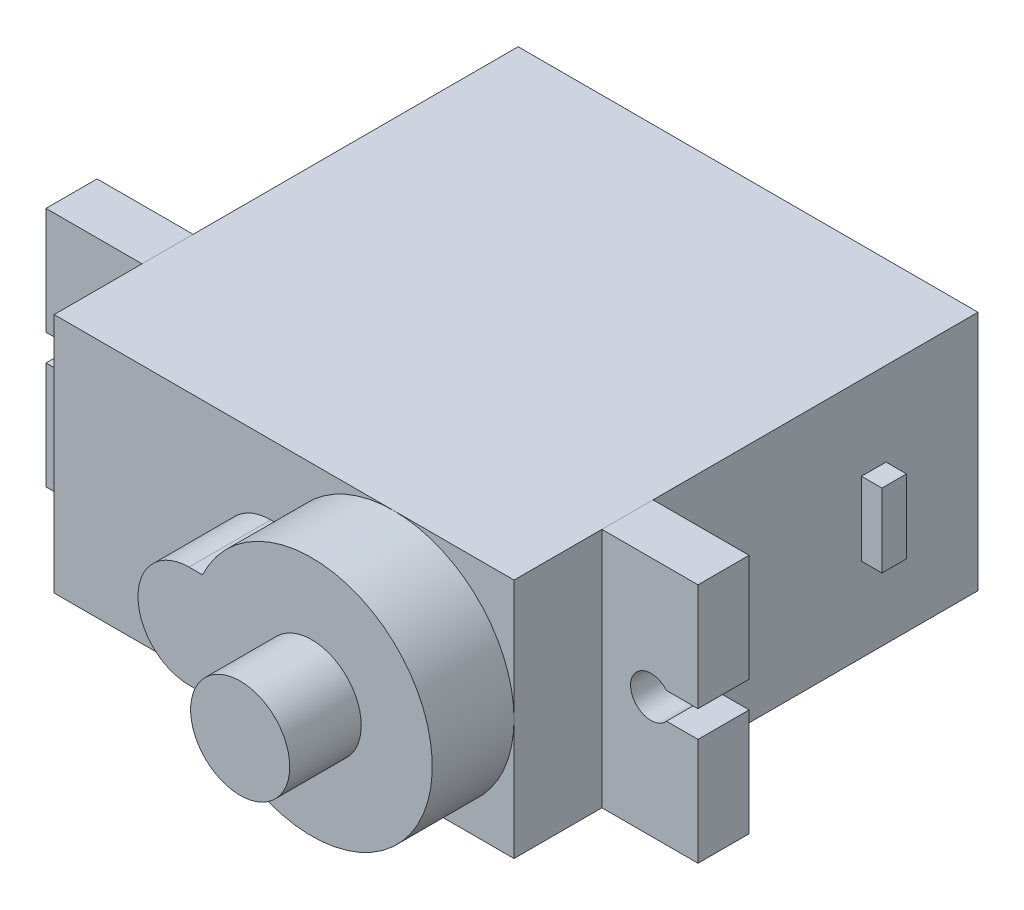
SolidWorks part; units mm, degrees
ref_plane "Alzado" through (0, 0, 0) normal (0, 0, 1) x (1, 0, 0)
ref_plane "Planta" through (0, 0, 0) normal (0, 1, 0) x (1, 0, 0)
ref_plane "Vista lateral" through (0, 0, 0) normal (1, 0, 0) x (0, 0, -1)
sketch "Croquis1" plane through (0, 0, 0) normal (0, 0, 1) x (1, 0, 0)
  line L1 (-11.25, -5.9) -> (11.25, -5.9)
  line L2 (-11.25, -5.9) -> (-11.25, 5.9)
  line L3 (-11.25, 5.9) -> (11.25, 5.9)
  line L4 (11.25, -5.9) -> (11.25, 5.9)
  line L5 (-11.25, -5.9) -> (11.25, 5.9) construction
  line L6 (-11.25, 5.9) -> (11.25, -5.9) construction
  point P0 (0, 0)
  dimension "D1" = 22.5
  dimension "D2" = 11.8
extrude "Saliente-Extruir2" add sketch "Croquis1" along normal blind 15.9
sketch "Croquis2" plane through (0, 0, 15.9) normal (0, 0, 1) x (1, 0, 0)
  line L0 (-11.25, -5.9) -> (11.25, -5.9) construction
  line L5 (0, 0) -> (0, 5.9) construction
  line L6 (11.25, 5.9) -> (-11.25, 5.9) construction
  line L7 (-11.25, 5.9) -> (-11.25, -5.9) construction
  line L8 (-11.25, 5.9) -> (-15.95, 5.9)
  line L9 (-11.25, 5.9) -> (-11.25, -5.9)
  line L10 (-11.25, -5.9) -> (-15.95, -5.9)
  line L11 (-15.95, 5.9) -> (-15.95, 0.65)
  line L12 (0, 0) -> (-15.95, 0) construction
  line L13 (-15.95, 0.65) -> (-14.4099, 0.65)
  line L15 (-14.4099, -0.65) -> (-15.95, -0.65)
  line L16 (-15.95, -0.65) -> (-15.95, -5.9)
  line L17 (15.95, -0.65) -> (15.95, -5.9)
  line L18 (14.4099, -0.65) -> (15.95, -0.65)
  line L19 (15.95, 0.65) -> (14.4099, 0.65)
  line L20 (15.95, 5.9) -> (15.95, 0.65)
  line L21 (11.25, -5.9) -> (15.95, -5.9)
  line L22 (11.25, 5.9) -> (11.25, -5.9)
  line L23 (11.25, 5.9) -> (15.95, 5.9)
  arc A0 (-14.4099, -0.65) -> (-14.4099, 0.65) centre (-13.65, 0) ccw
  arc A1 (14.4099, -0.65) -> (14.4099, 0.65) centre (13.65, 0) cw
  point P17 (-14.4099, -0.65)
  dimension "D2" = 2.3
  dimension "D3" = 2
  dimension "D1" = 4.7
  dimension "D4" = 1.3
  dimension "D5" = 0.65
extrude "Saliente-Extruir3" add sketch "Croquis2" along normal blind 2.5
sketch "Croquis3" plane through (0, 0, 0) normal (0, 0, -1) x (-1, 0, 0)
  line L1 (-11.25, -5.9) -> (11.25, -5.9)
  line L2 (-11.25, -5.9) -> (-11.25, 5.9)
  line L3 (-11.25, 5.9) -> (11.25, 5.9)
  line L4 (11.25, -5.9) -> (11.25, 5.9)
  line L5 (-11.25, -5.9) -> (11.25, 5.9) construction
  line L6 (-11.25, 5.9) -> (11.25, -5.9) construction
  point P0 (0, 0)
extrude "Saliente-Extruir4" add sketch "Croquis3" against normal blind 22.7
sketch "Croquis4" plane through (0, 0, 22.7) normal (0, 0, 1) x (1, 0, 0)
  line L0 (11.25, 5.9) -> (11.25, -5.9) construction
  line L1 (-11.25, 5.9) -> (11.25, 5.9) construction
  line L2 (11.25, -5.9) -> (-11.25, -5.9) construction
  line L3 (-0.65, 2.5) -> (0.0058, 2.5)
  line L4 (-0.65, -2.5) -> (0.0058, -2.5)
  line L5 (5.35, 0) -> (-0.65, 0) construction
  arc A0 (0.0058, -2.5) -> (0.0058, 2.5) centre (5.35, 0) ccw
  arc A1 (-0.65, 2.5) -> (-0.65, -2.5) centre (-0.65, 0) ccw
  point P1 (0, 2.5)
  point P10 (-3.15, 0)
  dimension "D1" = 5
  dimension "D2" = 8.5
extrude "Saliente-Extruir5" add sketch "Croquis4" along normal blind 4
sketch "Croquis5" plane through (0, 0, 26.7) normal (0, 0, 1) x (1, 0, 0)
  circle A0 centre (5.35, 0) radius 2.425
  dimension "D1" = 4.85
extrude "Saliente-Extruir6" add sketch "Croquis5" along normal blind 3.5
sketch "Croquis7" plane through (11.25, 0, 0) normal (1, 0, 0) x (0, 0, -1)
  line L0 (0, 0) -> (-5.1, 0) construction
  line L1 (0, -5.9) -> (0, 5.9) construction
  line L2 (-5.7, -1.8) -> (-4.5, -1.8)
  line L3 (-5.7, -1.8) -> (-5.7, 1.8)
  line L4 (-5.7, 1.8) -> (-4.5, 1.8)
  line L5 (-4.5, -1.8) -> (-4.5, 1.8)
  line L6 (-5.7, -1.8) -> (-4.5, 1.8) construction
  line L7 (-5.7, 1.8) -> (-4.5, -1.8) construction
  dimension "D1" = 1.2
  dimension "D2" = 4.5
  dimension "D3" = 3.6
extrude "Saliente-Extruir7" add sketch "Croquis7" along normal blind 1
